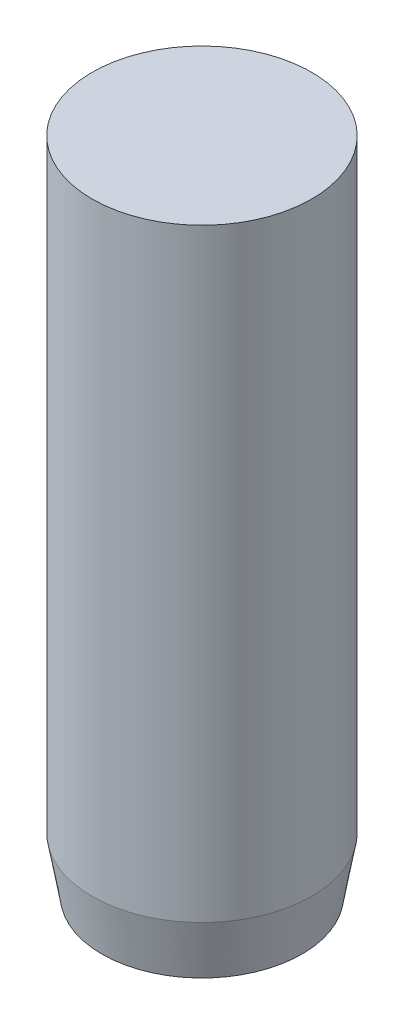
SolidWorks part; units mm, degrees
material "炭素鋼(普通)"
ref_plane "正面" through (0, 0, 0) normal (0, 0, 1) x (1, 0, 0)
ref_plane "平面" through (0, 0, 0) normal (0, 1, 0) x (1, 0, 0)
ref_plane "右側面" through (0, 0, 0) normal (1, 0, 0) x (0, 0, -1)
sketch "ｽｹｯﾁ1" plane through (0, 0, 0) normal (0, 1, 0) x (1, 0, 0)
  circle A0 centre (0, 0) radius 2
  dimension "D1" = 4
extrude "ﾎﾞｽ - 押し出し1" add sketch "ｽｹｯﾁ1" along normal blind 8
sketch "ｽｹｯﾁ2" plane through (0, 0, 0) normal (0, -1, 0) x (1, 0, 0)
  point P0 (0, 0)
sketch "ｽｹｯﾁ3" plane through (0, 8, 0) normal (0, 1, 0) x (1, 0, 0)
  circle A1 centre (0, 0) radius 2
  circle A2 centre (0, 0) radius 2
  dimension "D1" = 0
extrude "ﾎﾞｽ - 押し出し2" add sketch "ｽｹｯﾁ3" against normal blind 12
sketch "ｽｹｯﾁ4" plane through (0, 0, 0) normal (1, 0, 0) x (0, 0, -1)
  line L0 (1.8237, -4) -> (2, -3)
  line L1 (-2, -4) -> (2, -4) construction
  line L2 (2, -4) -> (2, 8) construction
  line L3 (2, -3) -> (2, -4)
  line L4 (2, -4) -> (2, 8) construction
  line L5 (2, -4) -> (1.8237, -4)
  line L6 (2, -4) -> (2, 8) construction
  line L7 (0, 0) -> (0, -4) construction
  dimension "D1" = 10
  dimension "D2" = 1
revolve "ｶｯﾄ - 回転1" cut sketch "ｽｹｯﾁ4" angle 360 about L7
